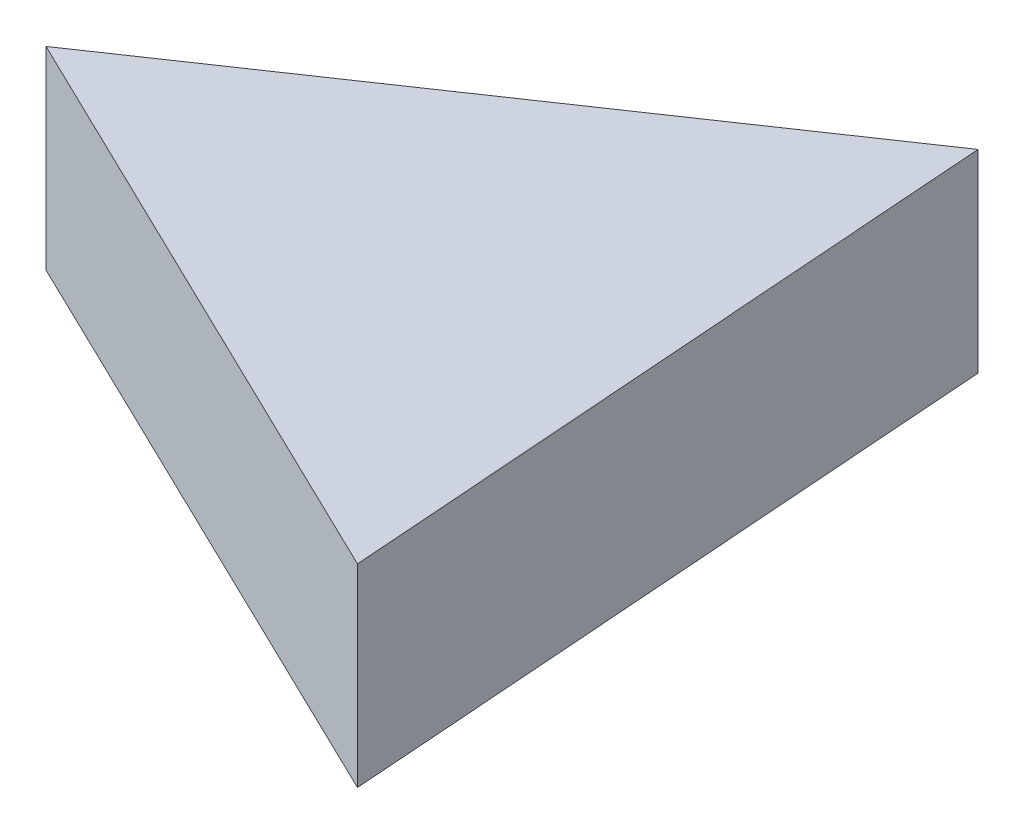
SolidWorks part; units mm, degrees
ref_plane "Front Plane" through (0, 0, 0) normal (0, 0, 1) x (1, 0, 0)
ref_plane "Top Plane" through (0, 0, 0) normal (0, 1, 0) x (1, 0, 0)
ref_plane "Right Plane" through (0, 0, 0) normal (1, 0, 0) x (0, 0, -1)
sketch "Sketch1" plane through (0, 0, 0) normal (0, 1, 0) x (1, 0, 0)
  line L1 (11.231, -16.5488) -> (8.7162, 18.0008)
  line L2 (8.7162, 18.0008) -> (-19.9472, -1.452)
  line L3 (-19.9472, -1.452) -> (11.231, -16.5488)
  circle A0 centre (0, 0) radius 10 construction
  dimension "D1" = 20
extrude "Boss-Extrude1" add sketch "Sketch1" against normal blind 10
sketch "Sketch2" plane through (0, 0, 0) normal (0, 1, 0) x (1, 0, 0)
  line L0 (-19.9472, -1.452) -> (11.231, -16.5488) construction
  line L1 (8.7162, 18.0008) -> (-19.9472, -1.452) construction
  line L2 (11.231, -16.5488) -> (8.7162, 18.0008) construction
  point P0 (-4.3581, -9.0004)
  point P1 (-5.6155, 8.2744)
  point P4 (9.9736, 0.726)
